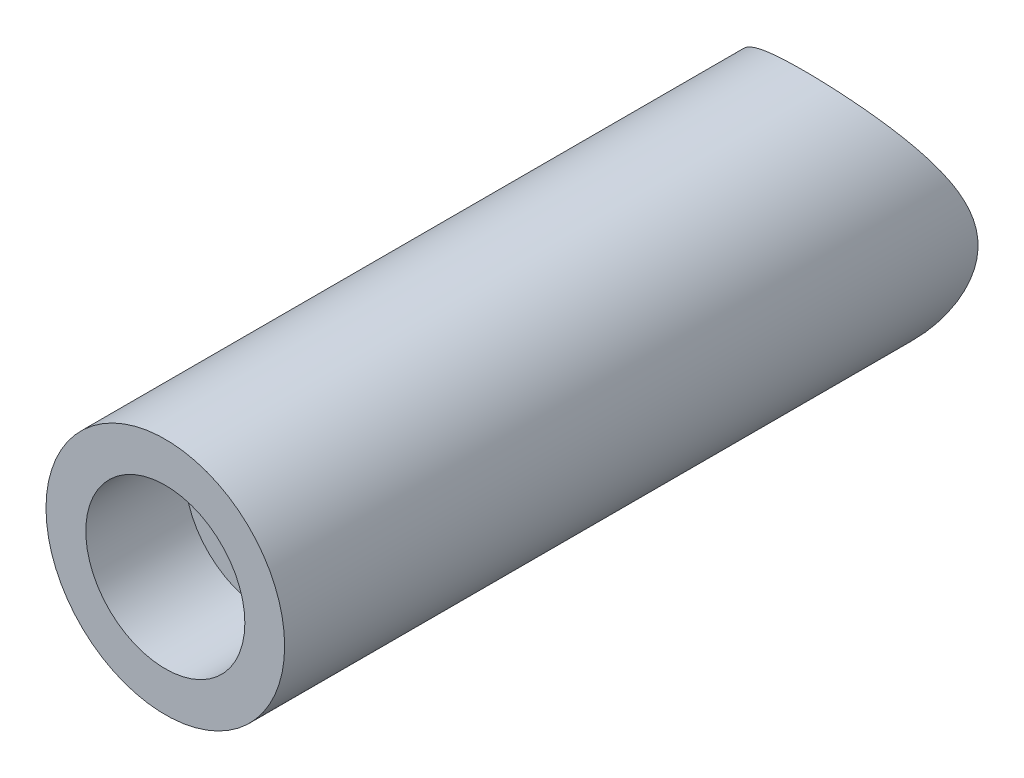
SolidWorks part; units mm, degrees
ref_plane "Front Plane" through (0, 0, 0) normal (0, 0, 1) x (1, 0, 0)
ref_plane "Top Plane" through (0, 0, 0) normal (0, 1, 0) x (1, 0, 0)
ref_plane "Right Plane" through (0, 0, 0) normal (1, 0, 0) x (0, 0, -1)
sketch "Sketch1" plane through (0, 0, 0) normal (0, 0, 1) x (1, 0, 0)
  circle A0 centre (0, 0) radius 114.3
  dimension "D1" = 228.6
extrude "Boss-Extrude1" add sketch "Sketch1" along normal blind 762
sketch "Sketch2" plane through (0, 0, 762) normal (0, 0, 1) x (1, 0, 0)
  circle A0 centre (0, 0) radius 76.2
  dimension "D1" = 152.4
extrude "Cut-Extrude1" cut sketch "Sketch2" against normal blind 94.996
sketch "Sketch6" plane through (0, 0, 0) normal (0, 1, 0) x (1, 0, 0)
  line L0 (114.3, 0) -> (-114.3, 0) construction
  circle A0 centre (0, 0) radius 150.368
  dimension "D1" = 300.736
extrude "Cut-Extrude2" cut sketch "Sketch6" along normal blind 241.046 and the other way blind 276.352
